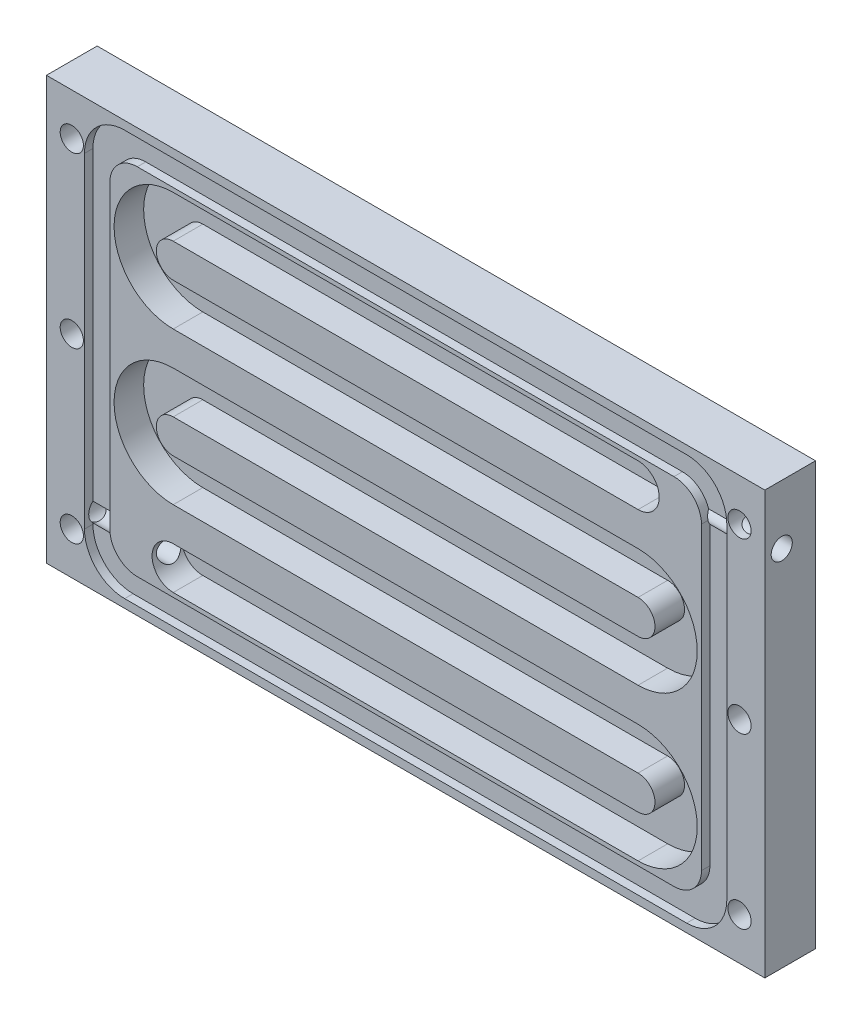
SolidWorks part; units mm, degrees
ref_plane "前视基准面" through (0, 0, 0) normal (0, 0, 1) x (1, 0, 0)
ref_plane "上视基准面" through (0, 0, 0) normal (0, 1, 0) x (1, 0, 0)
ref_plane "右视基准面" through (0, 0, 0) normal (1, 0, 0) x (0, 0, -1)
sketch "草图1" plane through (0, 0, 0) normal (0, 0, 1) x (1, 0, 0)
  line L0 (-85, -50) -> (85, -50)
  line L1 (85, -50) -> (85, 50)
  line L2 (85, 50) -> (-85, 50)
  line L3 (-85, 50) -> (-85, -50)
extrude "凸台-拉伸1" add sketch "草图1" along normal blind 12
ref_plane "基准面1" through (0, 0, 12) normal (0, 0, 1) x (1, 0, 0)
sketch "草图2" plane through (0, 0, 12) normal (0, 0, 1) x (1, 0, 0)
  line L0 (-55, -41) -> (55, -41)
  line L1 (55, -31) -> (-55, -31)
  line L2 (-55, -23) -> (55, -23)
  line L3 (55, -13) -> (-55, -13)
  line L4 (-55, -5) -> (55, -5)
  line L5 (55, 5) -> (-55, 5)
  line L6 (-55, 13) -> (55, 13)
  line L7 (55, 23) -> (-55, 23)
  line L8 (-55, 31) -> (55, 31)
  line L9 (55, 41) -> (-55, 41)
  arc A0 (55, -41) -> (55, -31) centre (55, -36) ccw
  arc A1 (-55, -31) -> (-55, -41) centre (-55, -36) ccw
  arc A2 (55, -23) -> (55, -13) centre (55, -18) ccw
  arc A3 (-55, -13) -> (-55, -23) centre (-55, -18) ccw
  arc A4 (55, -5) -> (55, 5) centre (55, 0) ccw
  arc A5 (-55, 5) -> (-55, -5) centre (-55, 0) ccw
  arc A6 (55, 13) -> (55, 23) centre (55, 18) ccw
  arc A7 (-55, 23) -> (-55, 13) centre (-55, 18) ccw
  arc A8 (55, 31) -> (55, 41) centre (55, 36) ccw
  arc A9 (-55, 41) -> (-55, 31) centre (-55, 36) ccw
extrude "切除-拉伸1" cut sketch "草图2" against normal blind 7
sketch "草图3" plane through (0, 0, 12) normal (0, 0, 1) x (1, 0, 0)
  line L0 (55, -13) -> (55, -23)
  line L1 (55, -31) -> (55, -41)
  line L2 (-55, -23) -> (-55, -13)
  line L3 (-55, -5) -> (-55, 5)
  line L4 (55, 23) -> (55, 13)
  line L5 (55, 5) -> (55, -5)
  line L6 (-55, 13) -> (-55, 23)
  line L7 (-55, 31) -> (-55, 41)
  arc A0 (55, -41) -> (55, -13) centre (55, -27) ccw
  arc A1 (55, -23) -> (55, -31) centre (55, -27) cw
  arc A2 (-55, 5) -> (-55, -23) centre (-55, -9) ccw
  arc A3 (-55, -13) -> (-55, -5) centre (-55, -9) cw
  arc A4 (55, -5) -> (55, 23) centre (55, 9) ccw
  arc A5 (55, 13) -> (55, 5) centre (55, 9) cw
  arc A6 (-55, 41) -> (-55, 13) centre (-55, 27) ccw
  arc A7 (-55, 23) -> (-55, 31) centre (-55, 27) cw
extrude "切除-拉伸2" cut sketch "草图3" against normal blind 7
sketch "草图4" plane through (0, 0, 12) normal (0, 0, 1) x (1, 0, 0)
  line L0 (-66.5, -48) -> (66.5, -48)
  line L1 (76, -38.5) -> (76, 38.5)
  line L2 (66.5, 48) -> (-66.5, 48)
  line L3 (-76, 38.5) -> (-76, -38.5)
  line L4 (-63.5, -42) -> (63.5, -42)
  line L5 (70, -35.5) -> (70, 35.5)
  line L6 (63.5, 42) -> (-63.5, 42)
  line L7 (-70, 35.5) -> (-70, -35.5)
  arc A0 (-76, -38.5) -> (-66.5, -48) centre (-66.5, -38.5) ccw
  arc A1 (66.5, -48) -> (76, -38.5) centre (66.5, -38.5) ccw
  arc A2 (76, 38.5) -> (66.5, 48) centre (66.5, 38.5) ccw
  arc A3 (-66.5, 48) -> (-76, 38.5) centre (-66.5, 38.5) ccw
  arc A4 (-70, -35.5) -> (-63.5, -42) centre (-63.5, -35.5) ccw
  arc A5 (63.5, -42) -> (70, -35.5) centre (63.5, -35.5) ccw
  arc A6 (70, 35.5) -> (63.5, 42) centre (63.5, 35.5) ccw
  arc A7 (-63.5, 42) -> (-70, 35.5) centre (-63.5, 35.5) ccw
extrude "切除-拉伸3" cut sketch "草图4" against normal blind 2
sketch "草图5" plane through (0, 0, 0) normal (0, 0, 1) x (1, 0, 0)
  circle A0 centre (-79, -40) radius 2.75
  circle A1 centre (-79, 0) radius 2.75
  circle A2 centre (-79, 40) radius 2.75
  circle A3 centre (79, -40) radius 2.75
  circle A4 centre (79, 0) radius 2.75
  circle A5 centre (79, 40) radius 2.75
extrude "切除-拉伸4" cut sketch "草图5" along normal through all
ref_plane "基准面2" through (-85, 0, 0) normal (1, 0, 0) x (0, 0, -1)
sketch "草图6" plane through (-85, 0, 0) normal (1, 0, 0) x (0, 0, -1)
  circle A0 centre (-8, -36) radius 3
extrude "切除-拉伸5" cut sketch "草图6" along normal blind 30
ref_plane "基准面3" through (85, 0, 0) normal (1, 0, 0) x (0, 0, -1)
sketch "草图7" plane through (85, 0, 0) normal (1, 0, 0) x (0, 0, -1)
  circle A0 centre (-8, 36) radius 2.5
extrude "切除-拉伸6" cut sketch "草图7" against normal blind 30
sketch "草图8" plane through (0, 0, 0) normal (0, 0, 1) x (1, 0, 0)
  circle A0 centre (0, 0) radius 2
extrude "切除-拉伸7" cut sketch "草图8" along normal blind 4
